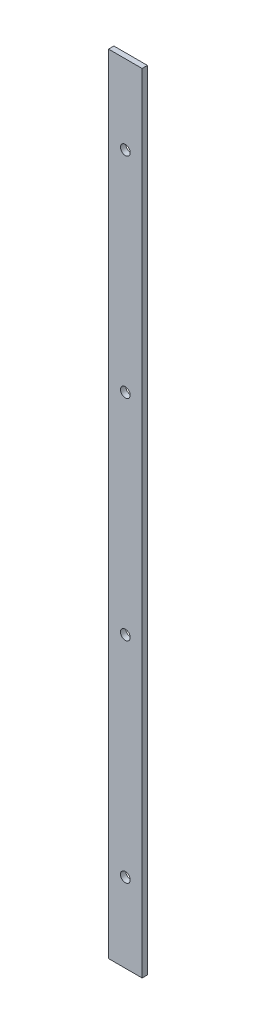
SolidWorks part; units mm, degrees
ref_plane "Front Plane" through (0, 0, 0) normal (0, 0, 1) x (1, 0, 0)
ref_plane "Top Plane" through (0, 0, 0) normal (0, 1, 0) x (1, 0, 0)
ref_plane "Right Plane" through (0, 0, 0) normal (1, 0, 0) x (0, 0, -1)
sketch "Sketch2" plane through (0, 0, 0) normal (0, 0, 1) x (1, 0, 0)
  line L1 (0, 0) -> (20, 0)
  line L2 (0, 0) -> (0, 469)
  line L3 (0, 469) -> (20, 469)
  line L4 (20, 0) -> (20, 469)
  dimension "D1" = 469
  dimension "D2" = 20
extrude "Boss-Extrude1" add sketch "Sketch2" along normal blind 3.175
hole_wizard "M5 Clearance Hole1" positions "3DSketch1" profile "Sketch3" hole size "M5" standard "ANSI Metric" end condition through all
sketch3d "3DSketch1"
  line L3 (10, 0, 3.175) -> (10, 47, 3.175) construction
  line L4 (0, 0, 3.175) -> (20, 0, 3.175) construction
  point P0 (10, 47, 3.175)
  dimension "D1" = 47
sketch "Sketch3" plane through (10, 47, 3.175) normal (1, 0, 0) x (0, -1, 0)
  line L0 (0, 0) -> (0, 3.175)
  line L1 (0, 3.175) -> (2.9, 3.175)
  line L2 (2.9, 3.175) -> (2.9, 0)
  line L5 (2.9, 0) -> (0, 0)
  line L11 (0, -6.35) -> (0, 107.95) construction
  dimension "Thru Hole Dia." = 5.8
  dimension "Thru Hole Depth" = 3.175
pattern_linear "LPattern1" count 4 spacing 125 along (0, 1, 0) of "M5 Clearance Hole1"
